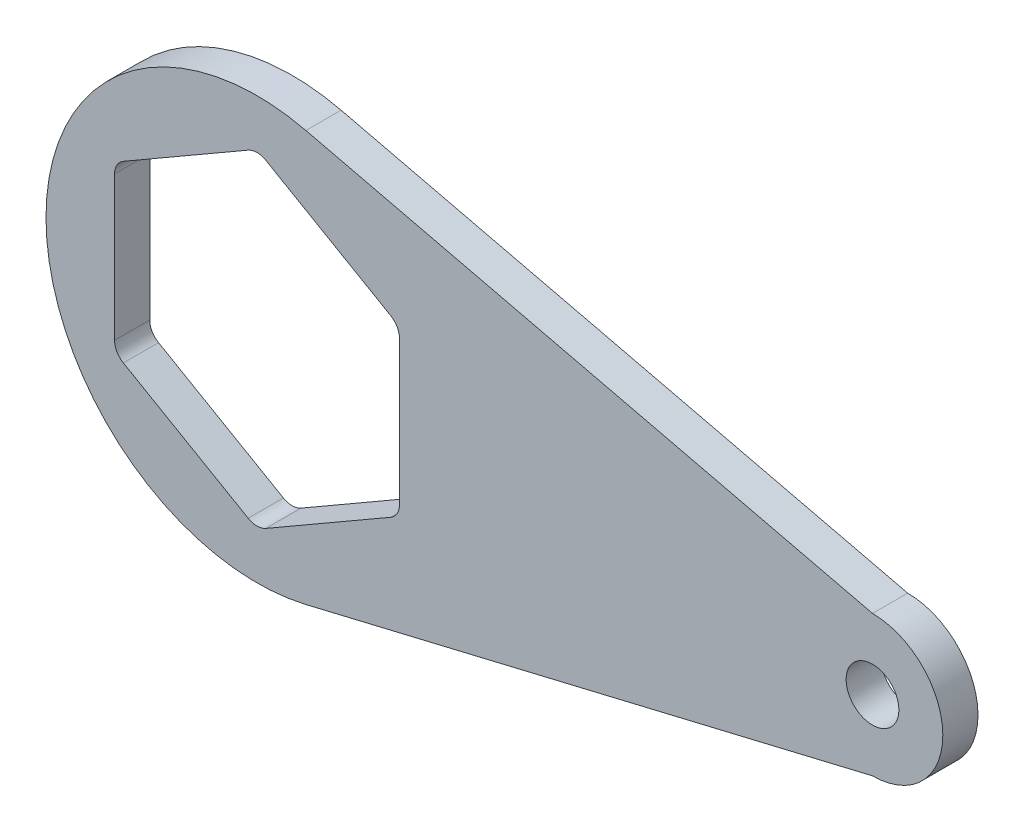
SolidWorks part; units mm, degrees
ref_plane "Front Plane" through (0, 0, 0) normal (0, 0, 1) x (1, 0, 0)
ref_plane "Top Plane" through (0, 0, 0) normal (0, 1, 0) x (1, 0, 0)
ref_plane "Right Plane" through (0, 0, 0) normal (1, 0, 0) x (0, 0, -1)
sketch "Sketch1" plane through (0, 0, 0) normal (0, 0, 1) x (1, 0, 0)
  line L0 (195, 0) -> (195, 64.8328) construction
  line L1 (40.5, 23.3827) -> (0, 46.7654)
  line L2 (0, 46.7654) -> (-40.5, 23.3827)
  line L3 (-40.5, 23.3827) -> (-40.5, -23.3827)
  line L4 (-40.5, -23.3827) -> (0, -46.7654)
  line L5 (0, -46.7654) -> (40.5, -23.3827)
  line L6 (40.5, -23.3827) -> (40.5, 23.3827)
  line L7 (175, 20) -> (13.9009, 58.3675)
  line L8 (175, -20) -> (13.9009, -58.3675)
  arc A0 (13.9009, 58.3675) -> (13.9009, -58.3675) centre (0, 0) ccw
  circle A1 centre (0, 0) radius 40.5 construction
  arc A2 (175, -20) -> (175, 20) centre (175, 0) ccw
  circle A3 centre (175, 0) radius 7.5
  dimension "D2" = 120
  dimension "D4" = 40
  dimension "D5" = 15
  dimension "D1" = 81
  dimension "D3" = 195
extrude "Boss-Extrude1" add sketch "Sketch1" along normal blind 10 contours L6 L1 L2 L3 L4 L5 | L7 A0 L8 A2 | A3
fillet "Fillet1" radius 5 6 edges at (-40.5, -23.3827, 5) (0, -46.7654, 5) (40.5, -23.3827, 5) (40.5, 23.3827, 5) (0, 46.7654, 5) (-40.5, 23.3827, 5)
